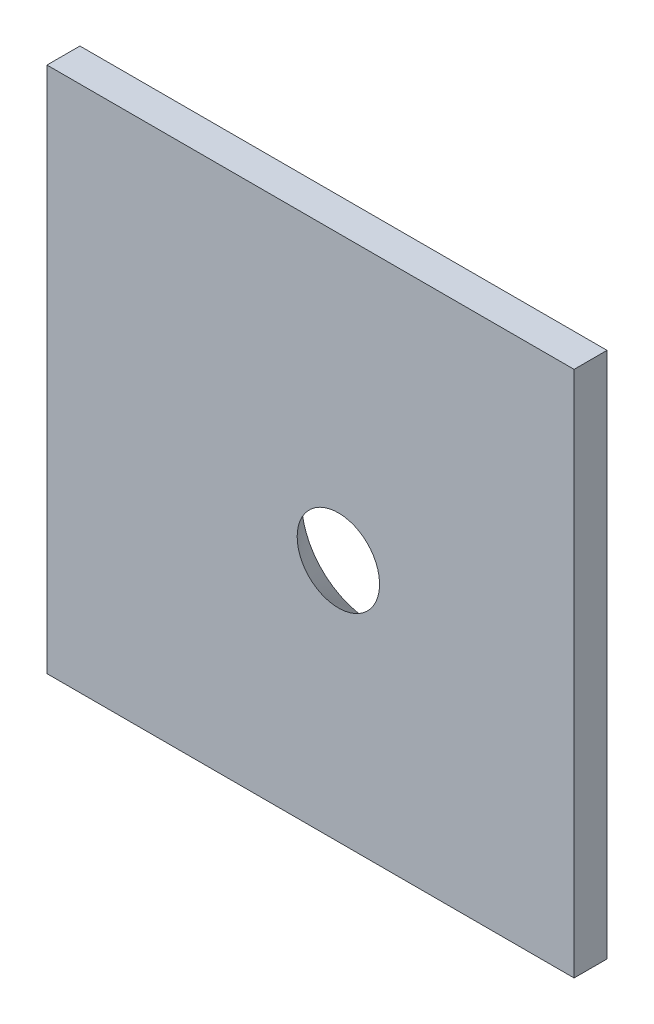
SolidWorks part; units mm, degrees
ref_plane "Front Plane" through (0, 0, 0) normal (0, 0, 1) x (1, 0, 0)
ref_plane "Top Plane" through (0, 0, 0) normal (0, 1, 0) x (1, 0, 0)
ref_plane "Right Plane" through (0, 0, 0) normal (1, 0, 0) x (0, 0, -1)
sketch "Sketch1" plane through (0, 0, 0) normal (0, 0, 1) x (1, 0, 0)
  line L1 (0, 0) -> (50.8, 0)
  line L2 (0, 0) -> (0, -50.8)
  line L3 (0, -50.8) -> (50.8, -50.8)
  line L4 (50.8, 0) -> (50.8, -50.8)
  point P5 (25.4, -25.4)
  dimension "D1" = 25.4
  dimension "D2" = 50.8
  dimension "D3" = 50.8
  dimension "D4" = 25.4
extrude "Boss-Extrude2" add sketch "Sketch1" along normal blind 3.175 contours L4 L3 L2 L1
hole_wizard "1/4 (0.25) Diameter Hole1" positions "3DSketch1" profile "Sketch2" hole size "1/4" standard "ANSI Inch" end condition through all
sketch3d "3DSketch1"
  point P0 (28.0836, -27.3052, 0)
sketch "Sketch2" plane through (28.0836, -27.3052, 0) normal (1, 0, 0) x (0, 1, 0)
  line L0 (0, 0) -> (0, 3.175)
  line L1 (0, 3.175) -> (3.175, 3.175)
  line L2 (3.175, 3.175) -> (3.175, 4.0907)
  line L3 (3.175, 4.0907) -> (6.731, 0)
  line L5 (6.731, 0) -> (0, 0)
  line L6 (-3.175, 4.0907) -> (-6.731, 0) construction
  line L11 (0, -6.35) -> (0, 107.95) construction
  dimension "Thru Hole Dia." = 6.35
  dimension "Thru Hole Depth" = 3.175
  dimension "Near C'Sink Dia." = 13.462
  dimension "Near C'Sink Angle" = 82
